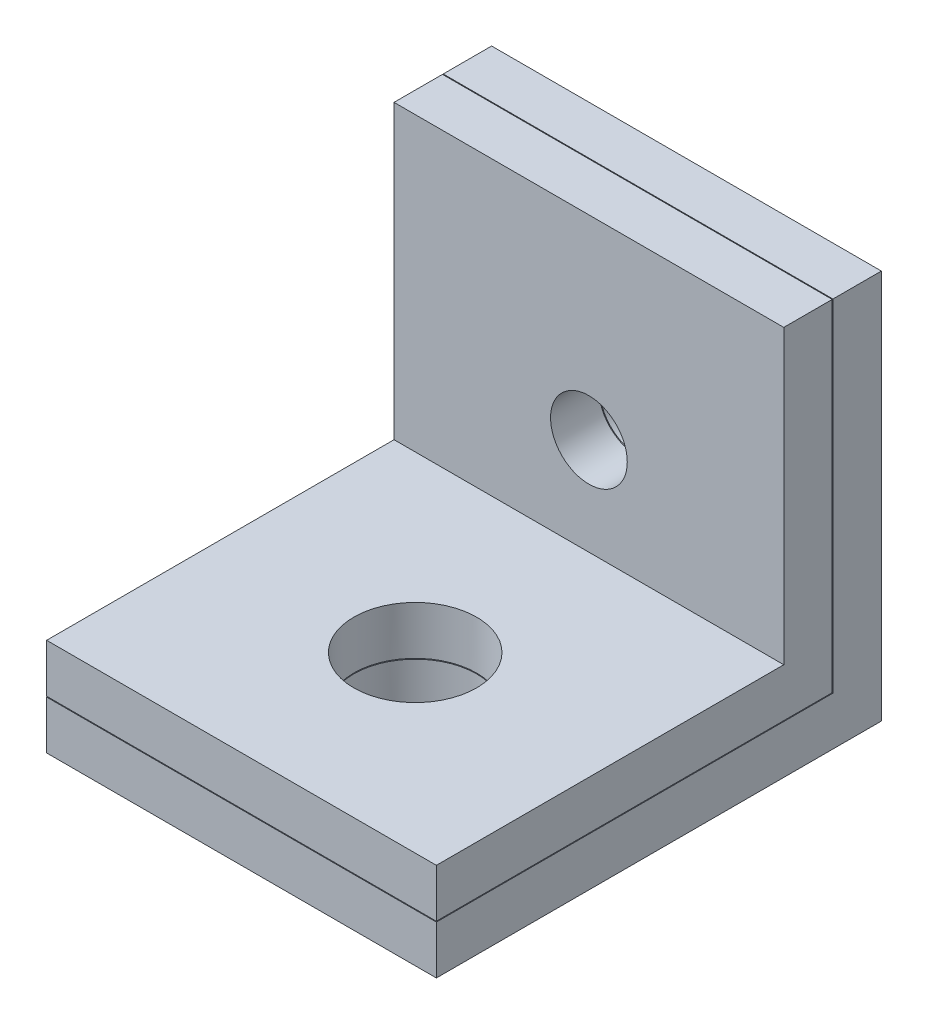
SolidWorks part; units mm, degrees
ref_plane "Alzado" through (0, 0, 0) normal (0, 0, 1) x (1, 0, 0)
ref_plane "Planta" through (0, 0, 0) normal (0, 1, 0) x (1, 0, 0)
ref_plane "Vista lateral" through (0, 0, 0) normal (1, 0, 0) x (0, 0, -1)
sketch "Croquis1" plane through (0, 0, 0) normal (1, 0, 0) x (0, 0, -1)
  line L0 (0, 0) -> (58, 0)
  line L1 (58, 0) -> (58, 50.8)
  line L2 (0, 6.31) -> (51.69, 6.31)
  line L3 (51.69, 6.31) -> (51.69, 50.8)
  line L4 (0, 6.31) -> (0, 0)
  line L5 (51.69, 50.8) -> (58, 50.8)
  dimension "D1" = 58
  dimension "D2" = 50.8
  dimension "D3" = 6.31
extrude "Saliente-Extruir1" add sketch "Croquis1" along normal blind 50.8
sketch "Croquis2" plane through (0, 0, 0) normal (-1, 0, 0) x (0, 0, 1)
  line L0 (-51.69, 50.8) -> (-51.59, 50.8) construction
  line L1 (-51.59, 50.8) -> (-51.59, 6.41)
  line L2 (-51.59, 6.41) -> (0, 6.41)
  line L3 (0, 6.41) -> (0, 6.31) construction
  line L4 (0, 6.41) -> (0, 12.72)
  line L5 (0, 12.72) -> (-45.28, 12.72)
  line L6 (-45.28, 12.72) -> (-45.28, 50.8)
  line L7 (-51.59, 50.8) -> (-45.28, 50.8)
  dimension "D1" = 0.1
  dimension "D2" = 0.1
  dimension "D3" = 6.31
  dimension "D4" = 6.31
extrude "Saliente-Extruir2" add sketch "Croquis2" against normal blind 50.8 separate body
sketch "Croquis3" plane through (0, 12.72, 0) normal (0, 1, 0) x (1, 0, 0)
  line L0 (0, 22.64) -> (50.8, 22.64) construction
  line L1 (0, 0) -> (0, 45.28) construction
  line L2 (50.8, 0) -> (50.8, 45.28) construction
  circle A0 centre (25.4, 22.64) radius 8
  dimension "D1" = 16
extrude "Cortar-Extruir1" cut sketch "Croquis3" against normal blind 50.8
sketch "Croquis4" plane through (0, 0, -58) normal (0, 0, -1) x (-1, 0, 0)
  line L0 (0, 25.4) -> (-50.8, 25.4) construction
  line L1 (0, 0) -> (0, 50.8) construction
  line L2 (-50.8, 0) -> (-50.8, 50.8) construction
  line L3 (-50.8, 25.4) -> (-25.4, 25.4) construction
  line L4 (-25.4, 25.4) -> (-25.4, 0) construction
  line L5 (-50.8, 0) -> (0, 0) construction
  circle A0 centre (-25.4, 25.4) radius 5
  dimension "D1" = 10
extrude "Cortar-Extruir2" cut sketch "Croquis4" against normal blind 24.525
